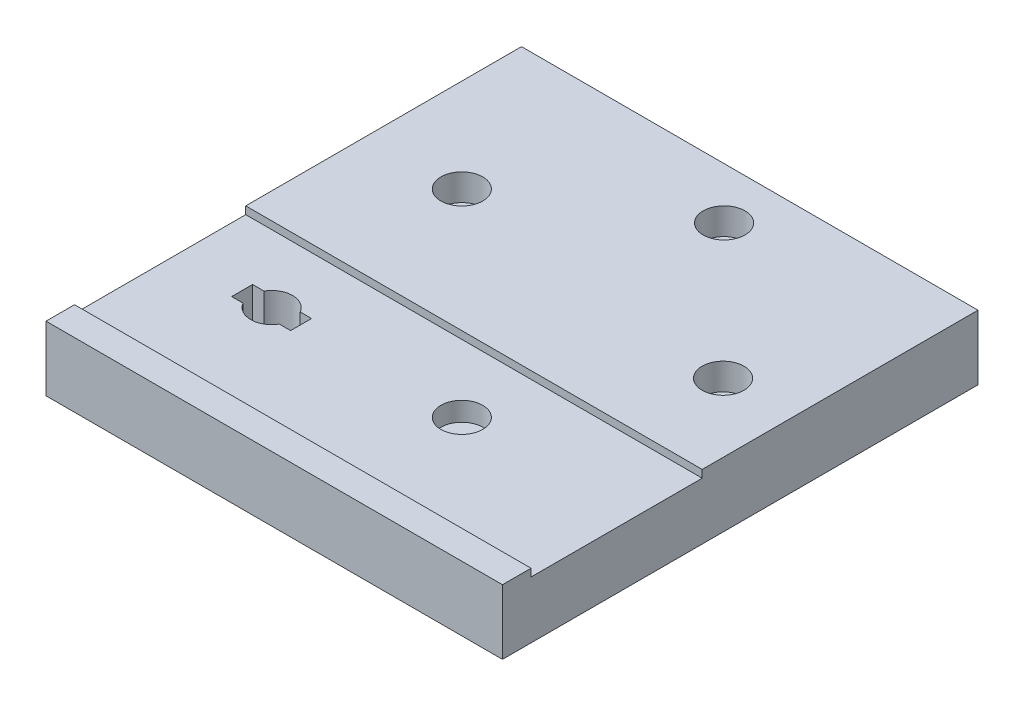
SolidWorks part; units mm, degrees
ref_plane "Front Plane" through (0, 0, 0) normal (0, 0, 1) x (1, 0, 0)
ref_plane "Top Plane" through (0, 0, 0) normal (0, 1, 0) x (1, 0, 0)
ref_plane "Right Plane" through (0, 0, 0) normal (1, 0, 0) x (0, 0, -1)
sketch "Sketch1" plane through (0, 0, 0) normal (0, 1, 0) x (1, 0, 0)
  line L1 (-60, -27.5) -> (60, -27.5)
  line L2 (-60, -27.5) -> (-60, 27.5)
  line L3 (-60, 27.5) -> (60, 27.5)
  line L4 (60, -27.5) -> (60, 27.5)
  line L5 (-60, -27.5) -> (60, 27.5) construction
  line L6 (-60, 27.5) -> (60, -27.5) construction
  point P0 (0, 0)
  dimension "D1" = 55
  dimension "D2" = 120
extrude "Boss-Extrude1" add sketch "Sketch1" along normal blind 5
sketch "Sketch2" plane through (0, 5, 0) normal (0, 1, 0) x (1, 0, 0)
  line L0 (60, -27.5) -> (60, 27.5) construction
  line L1 (-60, -27.5) -> (60, -27.5)
  line L2 (-60, -27.5) -> (-60, -20)
  line L3 (-60, -20) -> (60, -20)
  line L4 (60, -27.5) -> (60, -20)
  dimension "D1" = 7.5
extrude "Boss-Extrude2" add sketch "Sketch2" along normal blind 20
sketch "Sketch3" plane through (0, 5, 0) normal (0, 1, 0) x (1, 0, 0)
  line L0 (-60, 27.5) -> (-60, -20) construction
  line L1 (60, 27.5) -> (-60, 27.5)
  line L2 (60, 27.5) -> (60, 25)
  line L3 (60, 25) -> (-60, 25)
  line L4 (-60, 27.5) -> (-60, 25)
  dimension "D1" = 2.5
extrude "Boss-Extrude4" add sketch "Sketch3" along normal blind 20
sketch "Sketch8" plane through (-60, 0, 0) normal (-1, 0, 0) x (0, 0, 1)
  line L0 (-27.5, 0) -> (-27.5, 25)
  line L1 (-27.5, 25) -> (-25, 25)
  line L2 (-25, 25) -> (-25, 5)
  line L3 (-25, 5) -> (20, 5)
  line L4 (20, 5) -> (20, 25)
  line L5 (20, 25) -> (27.5, 25)
  line L6 (27.5, 25) -> (27.5, 0)
  line L7 (27.5, 0) -> (-27.5, 0)
extrude "Boss-Extrude5" add sketch "Sketch8" along normal blind 190
sketch "Sketch9" plane through (0, 0, -27.5) normal (0, 0, -1) x (-1, 0, 0)
  line L0 (-60, 0) -> (-60, 25)
  line L1 (-60, 25) -> (250, 25)
  line L2 (250, 25) -> (250, 0)
  line L3 (250, 0) -> (-60, 0)
extrude "Boss-Extrude6" add sketch "Sketch9" along normal blind 70
sketch "Sketch14" plane through (0, 0, 0) normal (0, -1, 0) x (-1, 0, 0)
  circle A0 centre (225.4453, 7.2552) radius 5.5
  circle A1 centre (175.4453, 7.2552) radius 5.5
  circle A2 centre (225.4453, 57.2552) radius 5.5
  circle A3 centre (148.0182, 48.5) radius 5.5
  circle A4 centre (183.2409, 83.9875) radius 5.5
  dimension "D1" = 11
  dimension "D3" = 11
  dimension "D5" = 11
  dimension "D6" = 11
  dimension "D8" = 11
  dimension "D2" = 50
  dimension "D4" = 50
  dimension "D7" = 50
extrude "Cut-Extrude5" cut sketch "Sketch14" against normal blind 153
sketch "Sketch15" plane through (60, 0, 0) normal (1, 0, 0) x (0, 0, -1)
  line L1 (-27.5, 25) -> (97.5, 25)
  line L2 (-27.5, 25) -> (-27.5, 0)
  line L3 (-27.5, 0) -> (97.5, 0)
  line L4 (97.5, 25) -> (97.5, 0)
extrude "Cut-Extrude6" cut sketch "Sketch15" against normal blind 190
sketch "Sketch16" plane through (0, 0, 0) normal (0, -1, 0) x (-1, 0, 0)
  line L1 (130, -27.5) -> (250, -27.5)
  line L2 (130, -27.5) -> (130, 97.5)
  line L3 (130, 97.5) -> (250, 97.5)
  line L4 (250, -27.5) -> (250, 97.5)
extrude "Boss-Extrude8" add sketch "Sketch16" along normal blind 10
sketch "Sketch17" plane through (0, 25, 0) normal (0, 1, 0) x (1, 0, 0)
  line L1 (-250, 97.5) -> (-130, 97.5)
  line L2 (-250, 97.5) -> (-250, -27.5)
  line L3 (-250, -27.5) -> (-130, -27.5)
  line L4 (-130, 97.5) -> (-130, -27.5)
extrude "Cut-Extrude7" cut sketch "Sketch17" against normal blind 18
sketch "Sketch18" plane through (0, 5, 0) normal (0, 1, 0) x (1, 0, 0)
  circle A0 centre (-225.4453, 7.2552) radius 5.5
extrude "Cut-Extrude8" cut sketch "Sketch18" against normal blind 31
sketch "Sketch19" plane through (0, 5, 0) normal (0, 1, 0) x (1, 0, 0)
  line L1 (-233.1953, 10.0052) -> (-217.6953, 10.0052)
  line L2 (-233.1953, 10.0052) -> (-233.1953, 4.5052)
  line L3 (-233.1953, 4.5052) -> (-217.6953, 4.5052)
  line L4 (-217.6953, 10.0052) -> (-217.6953, 4.5052)
  line L5 (-233.1953, 10.0052) -> (-217.6953, 4.5052) construction
  line L6 (-233.1953, 4.5052) -> (-217.6953, 10.0052) construction
  point P0 (-225.4453, 7.2552)
  dimension "D1" = 5.5
  dimension "D2" = 15.5
extrude "Cut-Extrude9" cut sketch "Sketch19" against normal blind 31
